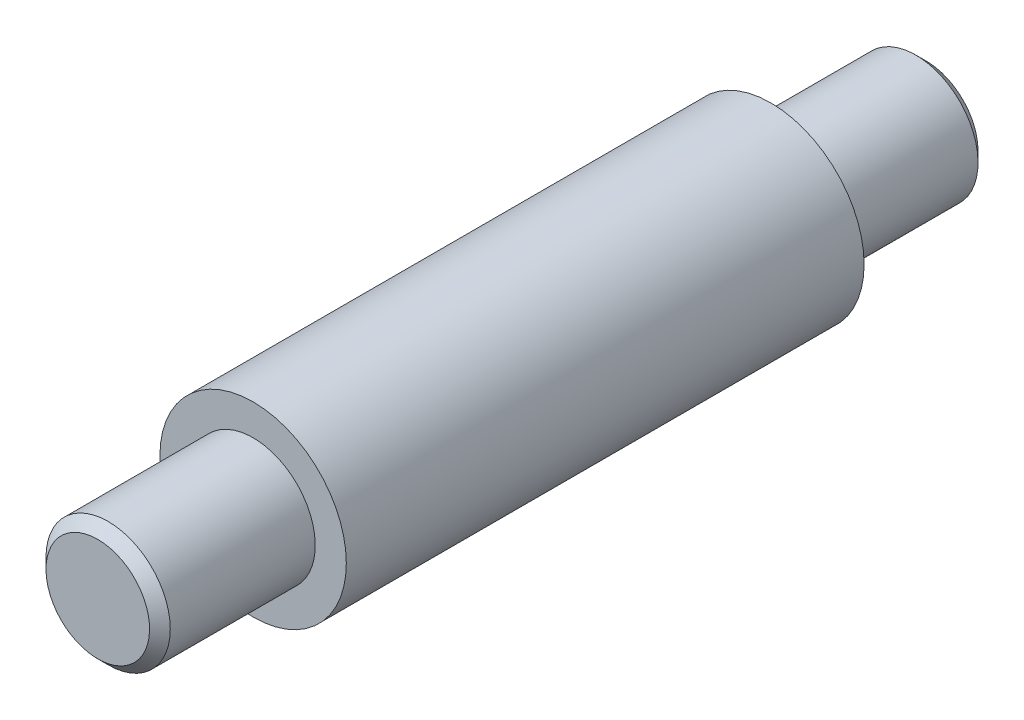
SolidWorks part; units mm, degrees
ref_plane "Front Plane" through (0, 0, 0) normal (0, 0, 1) x (1, 0, 0)
ref_plane "Top Plane" through (0, 0, 0) normal (0, 1, 0) x (1, 0, 0)
ref_plane "Right Plane" through (0, 0, 0) normal (1, 0, 0) x (0, 0, -1)
sketch "Sketch1" plane through (0, 0, 0) normal (1, 0, 0) x (0, 0, -1)
  line L0 (-25, 0) -> (25, 0)
  line L1 (25, 0) -> (40, 0)
  line L2 (40, 0) -> (40, 6)
  line L3 (40, 6) -> (25, 6)
  line L4 (25, 6) -> (25, 9)
  line L5 (25, 9) -> (-25, 9)
  line L7 (-25, 6) -> (-25, 9)
  line L8 (-40, 6) -> (-25, 6)
  line L9 (-40, 0) -> (-40, 6)
  line L10 (-25, 0) -> (-40, 0)
  dimension "D1" = 25
  dimension "D2" = 15
  dimension "D3" = 9
  dimension "D4" = 6
  dimension "D5" = 25
revolve "Revolve1" add sketch "Sketch1" angle 360 about L0
chamfer "Chamfer1" distance 1 angle 45 2 edges at (0, -6, 40) (0, -6, -40)
